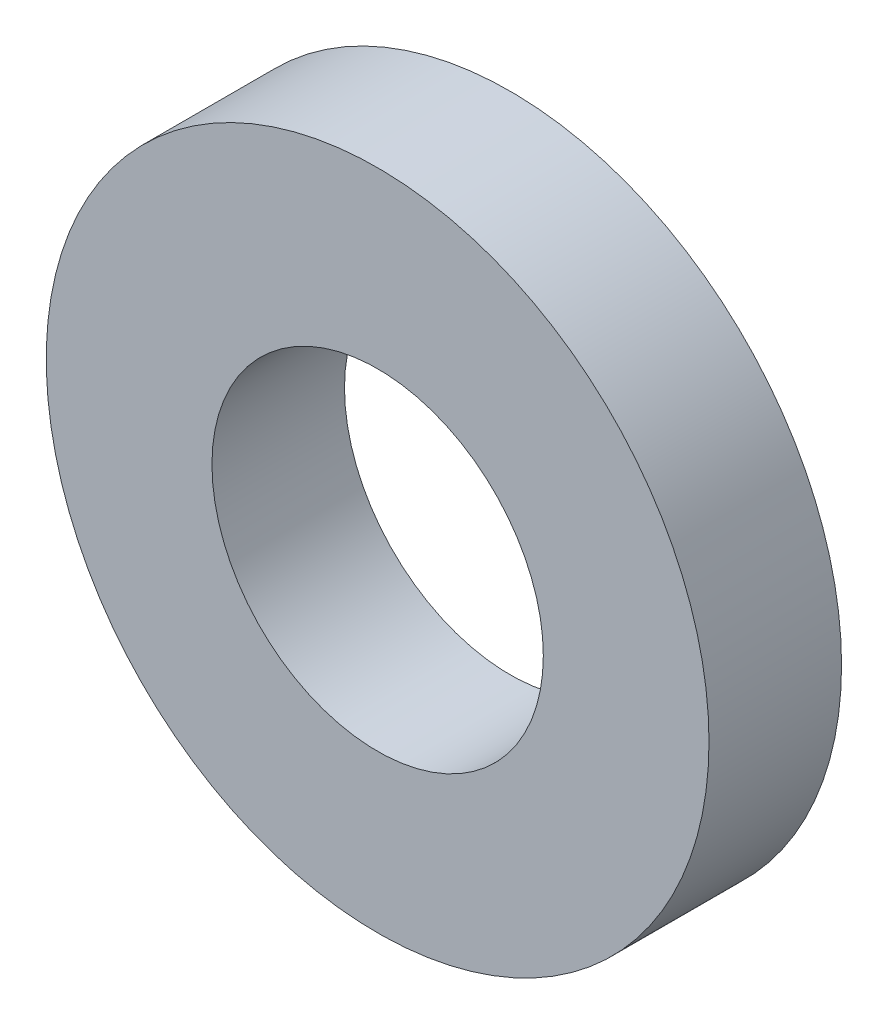
SolidWorks part; units mm, degrees
ref_plane "Front Plane" through (0, 0, 0) normal (0, 0, 1) x (1, 0, 0)
ref_plane "Top Plane" through (0, 0, 0) normal (0, 1, 0) x (1, 0, 0)
ref_plane "Right Plane" through (0, 0, 0) normal (1, 0, 0) x (0, 0, -1)
sketch "Sketch1" plane through (0, 0, 0) normal (0, 0, 1) x (1, 0, 0)
  circle A0 centre (0, 0) radius 15.875
  circle A1 centre (0, -0.4037) radius 7.9375
  dimension "D1" = 31.75
  dimension "D2" = 15.875
extrude "Boss-Extrude1" add sketch "Sketch1" along normal blind 6.35
